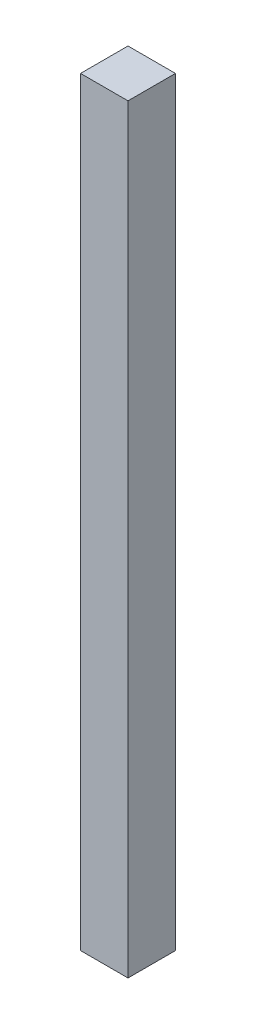
SolidWorks part; units mm, degrees
ref_plane "Front" through (0, 0, 0) normal (0, 0, 1) x (1, 0, 0)
ref_plane "Top" through (0, 0, 0) normal (0, 1, 0) x (1, 0, 0)
ref_plane "Right" through (0, 0, 0) normal (1, 0, 0) x (0, 0, -1)
sketch "Esquisse1" plane through (0, 0, 0) normal (0, 1, 0) x (1, 0, 0)
  line L1 (0, 0) -> (50, 0)
  line L2 (0, 0) -> (0, 50)
  line L3 (0, 50) -> (50, 50)
  line L4 (50, 0) -> (50, 50)
  dimension "D1" = 50
  dimension "D2" = 50
extrude "Boss.-Extru.1" add sketch "Esquisse1" along normal blind 800
sketch "Esquisse2" [suppressed] plane through (0, 0, 0) normal (0, 0, 1) x (1, 0, 0)
  line L0 (25, 0) -> (25, 60) construction
  line L1 (0, 0) -> (50, 0) construction
  circle A0 centre (25, 60) radius 10
  dimension "D1" = 20
  dimension "D2" = 40
extrude "Enlèv. mat.-Extru.1" [suppressed] cut sketch "Esquisse2" against normal through all both and the other way through all
